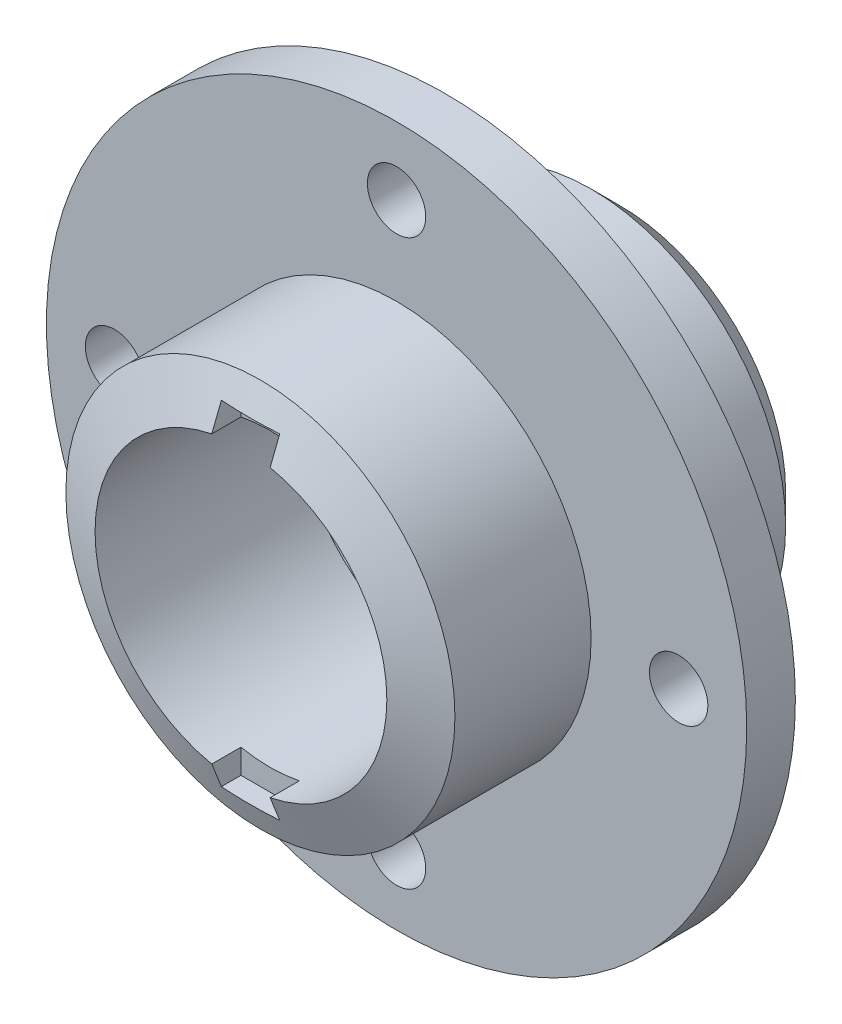
SolidWorks part; units mm, degrees
ref_plane "Front Plane" through (0, 0, 0) normal (0, 0, 1) x (1, 0, 0)
ref_plane "Top Plane" through (0, 0, 0) normal (0, 1, 0) x (1, 0, 0)
ref_plane "Right Plane" through (0, 0, 0) normal (1, 0, 0) x (0, 0, -1)
sketch "Sketch1" plane through (0, 0, 0) normal (0, 1, 0) x (1, 0, 0)
  line L0 (24, 78) -> (24, 72)
  line L1 (24, 72) -> (34, 72)
  line L2 (34, 72) -> (34, 42)
  line L3 (34, 42) -> (30, 42)
  line L4 (30, 42) -> (30, 0)
  line L5 (30, 0) -> (40, 4)
  line L6 (40, 4) -> (40, 32)
  line L7 (40, 32) -> (72, 32)
  line L8 (72, 32) -> (72, 42)
  line L9 (72, 42) -> (40, 42)
  line L10 (40, 42) -> (40, 72)
  line L11 (40, 72) -> (34, 78)
  line L12 (34, 78) -> (24, 78)
  line L13 (0, 0) -> (0, 71.2513) construction
  dimension "D1" = 10
  dimension "D2" = 36
  dimension "D3" = 32
  dimension "D4" = 4
  dimension "D5" = 6
  dimension "D6" = 34
  dimension "D7" = 30
  dimension "D8" = 40
  dimension "D9" = 72
  dimension "D10" = 24
revolve "Revolve1" add sketch "Sketch1" angle 360 about L13
sketch "Sketch2" plane through (0, 0, -42) normal (0, 0, -1) x (-1, 0, 0)
  circle A0 centre (0, 0) radius 58 construction
  circle A1 centre (0, 58) radius 6
  circle A2 centre (58, 0) radius 6
  circle A3 centre (0, -58) radius 6
  circle A4 centre (-58, 0) radius 6
  point P14 (0, 0)
  dimension "D1" = 116
  dimension "D2" = 12
  dimension "D3" = 4
extrude "Cut-Extrude1" cut sketch "Sketch2" against normal through all both
ref_plane "Plane1" through (0, 0, 0) normal (0, 0, 1) x (1, 0, 0)
sketch "Sketch5" plane through (0, 0, 0) normal (0, 0, 1) x (1, 0, 0)
  line L0 (-26.9684, 0) -> (0, 0) construction
  line L1 (-6, 25.5893) -> (6, 25.5893)
  line L2 (-6, 25.5893) -> (-6, 34.4107)
  line L3 (-6, 34.4107) -> (6, 34.4107)
  line L4 (6, 25.5893) -> (6, 34.4107)
  line L5 (-6, 25.5893) -> (6, 34.4107) construction
  line L6 (-6, 34.4107) -> (6, 25.5893) construction
  line L7 (6, -25.5893) -> (6, -34.4107)
  line L8 (-6, -25.5893) -> (-6, -34.4107)
  line L9 (-6, -34.4107) -> (6, -34.4107)
  line L10 (-6, -25.5893) -> (6, -25.5893)
  circle A0 centre (0, 0) radius 30 construction
  point P0 (0, 30)
  dimension "D1" = 12
extrude "Cut-Extrude3" cut sketch "Sketch5" against normal blind 6
